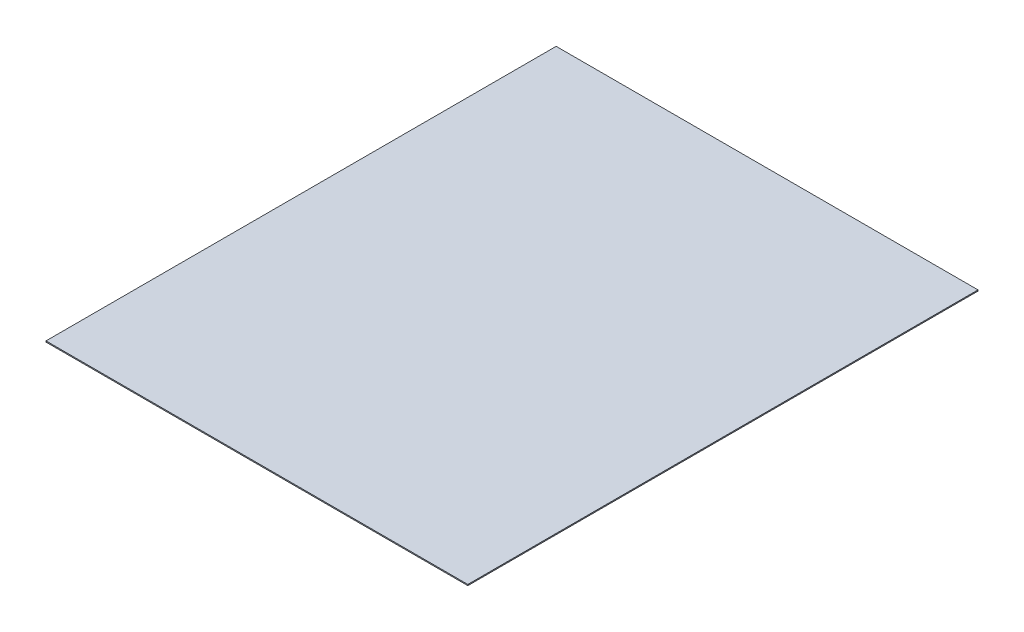
SolidWorks part; units mm, degrees
ref_plane "Front Plane" through (0, 0, 0) normal (0, 0, 1) x (1, 0, 0)
ref_plane "Top Plane" through (0, 0, 0) normal (0, 1, 0) x (1, 0, 0)
ref_plane "Right Plane" through (0, 0, 0) normal (1, 0, 0) x (0, 0, -1)
other "Configuration Table"
sketch "Sketch1" plane through (0, 0, 0) normal (0, 0, 1) x (1, 0, 0)
  line L1 (16.7, 5) -> (601.3, 5)
  line L2 (16.7, 5) -> (16.7, 6.5)
  line L3 (16.7, 6.5) -> (601.3, 6.5)
  line L4 (601.3, 5) -> (601.3, 6.5)
extrude "CEK_icecek_tepsi_taban_saci_1.5_1" add sketch "Sketch1" against normal blind 707 from offset 3 separate body
